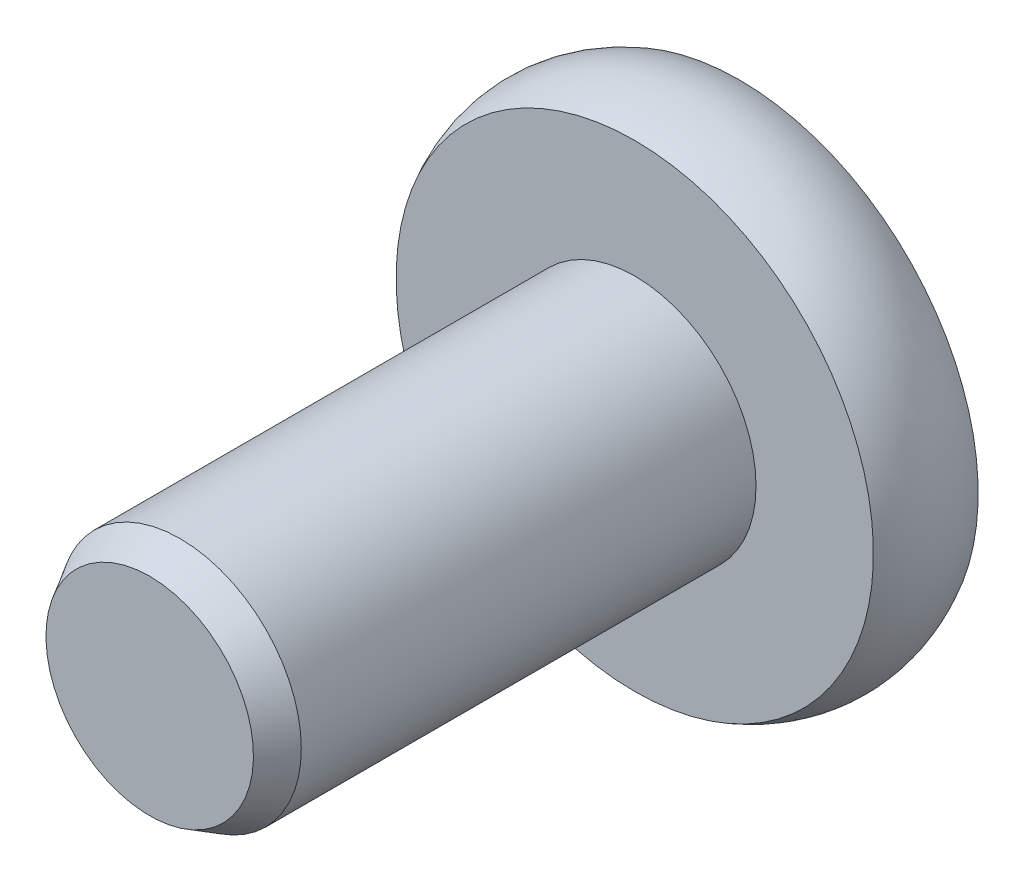
SolidWorks part; units mm, degrees
ref_plane "Front" through (0, 0, 0) normal (0, 0, 1) x (1, 0, 0)
ref_plane "Top" through (0, 0, 0) normal (0, 1, 0) x (1, 0, 0)
ref_plane "Right" through (0, 0, 0) normal (1, 0, 0) x (0, 0, -1)
sketch "Sketch1" plane through (0, 0, 0) normal (1, 0, 0) x (0, 0, -1)
  line L0 (-3.8608, 0) -> (3.8608, 0) construction
  line L2 (2.4892, 3.302) -> (2.4892, -3.302) construction
  line L3 (-3.8608, 1.5875) -> (-3.8608, -1.5875) construction
  point P8 (0, 0)
  point P9 (2.4892, 0)
sketch "Sketch2" plane through (0, 0, 0) normal (1, 0, 0) x (0, 0, -1)
  line L0 (3.8608, 3.302) -> (3.8608, 0) construction
  line L1 (3.8608, 3.302) -> (2.4892, 3.302) construction
  line L2 (2.4892, 3.1242) -> (3.8608, 3.1242) construction
  line L3 (2.4892, 3.302) -> (2.4892, -3.302) construction
  line L4 (2.4892, 1.5875) -> (-3.8608, 1.5875)
  line L5 (-3.8608, 1.5875) -> (-3.8608, 0)
  line L6 (-3.8608, 1.5875) -> (-3.8608, -1.5875) construction
  line L7 (-3.8608, 0) -> (3.8608, 0)
  line L8 (2.4892, 1.5875) -> (2.4892, 3.1242)
  line L9 (3.8608, 0) -> (3.8608, 3.1242)
  line L10 (2.4892, 3.302) -> (2.4892, 1.5875) construction
  line L11 (3.175, 3.302) -> (3.175, -1.651) construction
  arc A0 (2.4892, 3.1242) -> (3.8608, 3.1242) centre (3.175, 1.8905) cw
  dimension "D1" = 0.1778
revolve "Revolve1" add sketch "Sketch2" angle 360 about L7
chamfer "Chamfer1" distance 0.3969 angle 30 1 edges at (0, -1.5875, 3.8608)
equation "\"D1@Chamfer1\"=\"Diameter@Sketch1\"/8"
